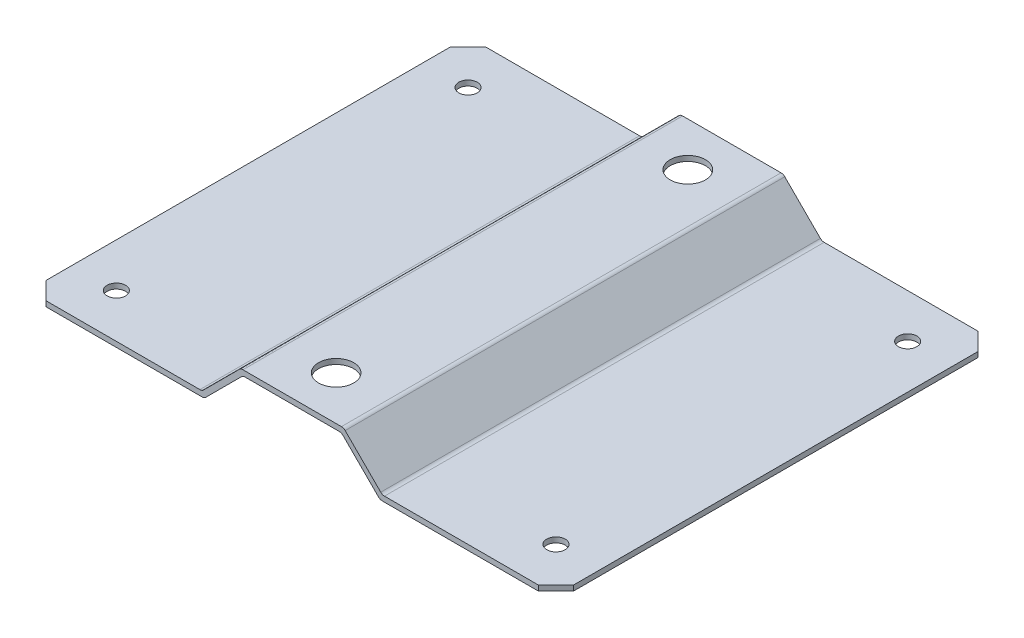
SolidWorks part; units mm, degrees
material "Q235"
ref_plane "前视基准面" through (0, 0, 0) normal (0, 0, 1) x (1, 0, 0)
ref_plane "上视基准面" through (0, 0, 0) normal (0, 1, 0) x (1, 0, 0)
ref_plane "右视基准面" through (0, 0, 0) normal (1, 0, 0) x (0, 0, -1)
sketch "草图1" plane through (0, 0, 0) normal (0, 0, 1) x (1, 0, 0)
  line L0 (0, 0) -> (100, 0)
  line L1 (100, 0) -> (122, 22)
  line L2 (122, 22) -> (178, 22)
  line L3 (178, 22) -> (200, 0)
  line L4 (200, 0) -> (300, 0)
  line L5 (300, 0) -> (300, 3)
  line L6 (300, 3) -> (201.2426, 3)
  line L7 (201.2426, 3) -> (179.2426, 25)
  line L8 (179.2426, 25) -> (120.7574, 25)
  line L9 (120.7574, 25) -> (98.7574, 3)
  line L10 (98.7574, 3) -> (0, 3)
  line L11 (0, 3) -> (0, 0)
  line L12 (150, 62.8623) -> (150, -31.1411) construction
  dimension "D1" = 300
  dimension "D2" = 3
  dimension "D3" = 3
  dimension "D4" = 3
  dimension "D5" = 135
  dimension "D6" = 3
  dimension "D7" = 3
  dimension "D8" = 135
  dimension "D9" = 25
  dimension "D10" = 150
  dimension "D11" = 50
  dimension "D12" = 50
extrude "凸台-拉伸1" add sketch "草图1" along normal blind 250
hole_wizard "Ø3.0 (3) 直径孔1" positions "草图3" profile "草图2" hole size "Ø3.0" standard "GB"
sketch "草图3" plane through (0, 22, 0) normal (0, -1, 0) x (-1, 0, 0)
  line L0 (-122, -250) -> (-178, -250) construction
  line L1 (-300, -250) -> (-300, 0) construction
  point P0 (-150, -225)
  point P2 (-150, -25)
  dimension "D1" = 200
  dimension "D2" = 25
  dimension "D3" = 150
  dimension "D4" = 150
sketch "草图2" plane through (150, 22, 225) normal (1, 0, 0) x (0, 0, -1)
  line L0 (0, 0) -> (0, 48.5086)
  line L1 (0, 48.5086) -> (10, 42.5)
  line L2 (10, 42.5) -> (10, 0)
  line L5 (10, 0) -> (0, 0)
  line L10 (0, 48.5086) -> (-10, 42.5) construction
  line L11 (0, -6.35) -> (0, 107.95) construction
  dimension "孔直径" = 20
  dimension "孔深度" = 42.5
  dimension "导头角度" = 118
fillet "圆角1" radius 3 8 edges at (120.7574, 25, 125) (200, 0, 125) (178, 22, 125) (122, 22, 125) (100, 0, 125) (201.2426, 3, 125) (179.2426, 25, 125) (98.7574, 3, 125)
hole_wizard "Ø10.5 (10.5) 直径孔1" positions "草图4" profile "草图5" hole size "Ø10.5" standard "GB" end condition through all
sketch "草图4" plane through (0, 0, 0) normal (0, -1, 0) x (-1, 0, 0)
  line L0 (0, -250) -> (-98.7574, -250) construction
  line L1 (0, 0) -> (-98.7574, 0) construction
  line L2 (0, -250) -> (0, 0) construction
  line L3 (-300, -250) -> (-300, 0) construction
  line L4 (-201.2426, -250) -> (-300, -250) construction
  line L5 (-201.2426, 0) -> (-300, 0) construction
  point P0 (-25, -225)
  point P2 (-25, -25)
  point P4 (-275, -225)
  point P6 (-275, -25)
  dimension "D1" = 25
  dimension "D2" = 25
  dimension "D3" = 25
  dimension "D4" = 25
  dimension "D5" = 25
  dimension "D6" = 25
  dimension "D7" = 25
  dimension "D8" = 25
sketch "草图5" plane through (25, 0, 225) normal (1, 0, 0) x (0, 0, -1)
  line L0 (0, 0) -> (0, 25)
  line L1 (0, 25) -> (5.25, 25)
  line L2 (5.25, 25) -> (5.25, 0)
  line L5 (5.25, 0) -> (0, 0)
  line L11 (0, -6.35) -> (0, 107.95) construction
  dimension "通孔孔直径" = 10.5
  dimension "通孔孔深度" = 25
chamfer "倒角1" distance 10 angle 45 4 edges at (300, 1.5, 0) (0, 1.5, 0) (0, 1.5, 250) (300, 1.5, 250)
